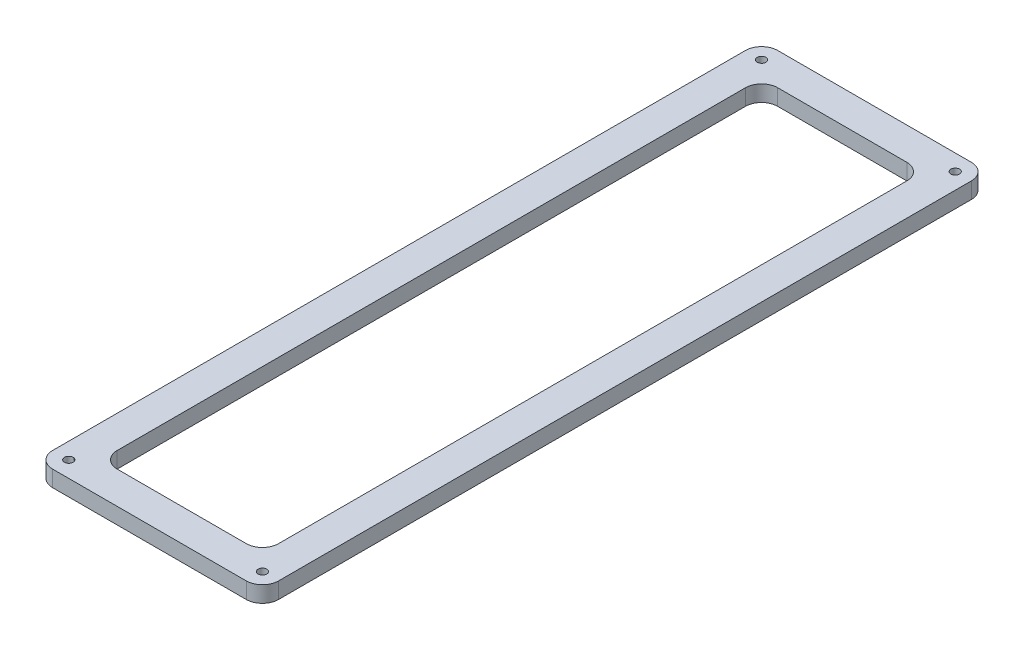
SolidWorks part; units mm, degrees
ref_plane "Front Plane" through (0, 0, 0) normal (0, 0, 1) x (1, 0, 0)
ref_plane "Top Plane" through (0, 0, 0) normal (0, 1, 0) x (1, 0, 0)
ref_plane "Right Plane" through (0, 0, 0) normal (1, 0, 0) x (0, 0, -1)
sketch "Sketch1" plane through (0, 0, 0) normal (0, 1, 0) x (1, 0, 0)
  line L0 (0, -3.175) -> (38.1, -3.175)
  line L1 (41.275, 0) -> (41.275, 136.3137)
  line L2 (38.1, 139.4887) -> (0, 139.4887)
  line L3 (-3.175, 136.3137) -> (-3.175, 0)
  line L4 (6.35, 133.1387) -> (31.75, 133.1387)
  line L5 (34.925, 129.9637) -> (34.925, 6.35)
  line L6 (31.75, 3.175) -> (6.35, 3.175)
  line L7 (3.175, 6.35) -> (3.175, 129.9637)
  arc A0 (31.75, 133.1387) -> (34.925, 129.9637) centre (31.75, 129.9637) cw
  arc A1 (6.35, 133.1387) -> (3.175, 129.9637) centre (6.35, 129.9637) ccw
  arc A2 (6.35, 3.175) -> (3.175, 6.35) centre (6.35, 6.35) cw
  arc A3 (34.925, 6.35) -> (31.75, 3.175) centre (31.75, 6.35) cw
  arc A4 (0, 139.4887) -> (-3.175, 136.3137) centre (0, 136.3137) ccw
  arc A5 (41.275, 136.3137) -> (38.1, 139.4887) centre (38.1, 136.3137) ccw
  arc A6 (38.1, -3.175) -> (41.275, 0) centre (38.1, 0) ccw
  arc A7 (0, -3.175) -> (-3.175, 0) centre (0, 0) cw
  circle A8 centre (0, 136.3137) radius 0.8509
  circle A9 centre (38.1, 136.3137) radius 0.8509
  circle A10 centre (0, 0) radius 0.8509
  circle A11 centre (38.1, 0) radius 0.8509
  point P4 (0, 136.3137)
  point P6 (38.1, 136.3137)
  point P7 (38.1, 0)
  point P8 (0, 0)
  dimension "D11" = 3.175
  dimension "D12" = 1.7018
  dimension "D1" = 3.175
  dimension "D2" = 3.175
  dimension "D3" = 3.175
  dimension "D4" = 3.175
  dimension "D5" = 3.175
  dimension "D6" = 3.175
  dimension "D7" = 3.175
  dimension "D8" = 38.1
  dimension "D9" = 3.175
  dimension "D10" = 136.3137
extrude "Boss-Extrude1" add sketch "Sketch1" along normal blind 3.175
